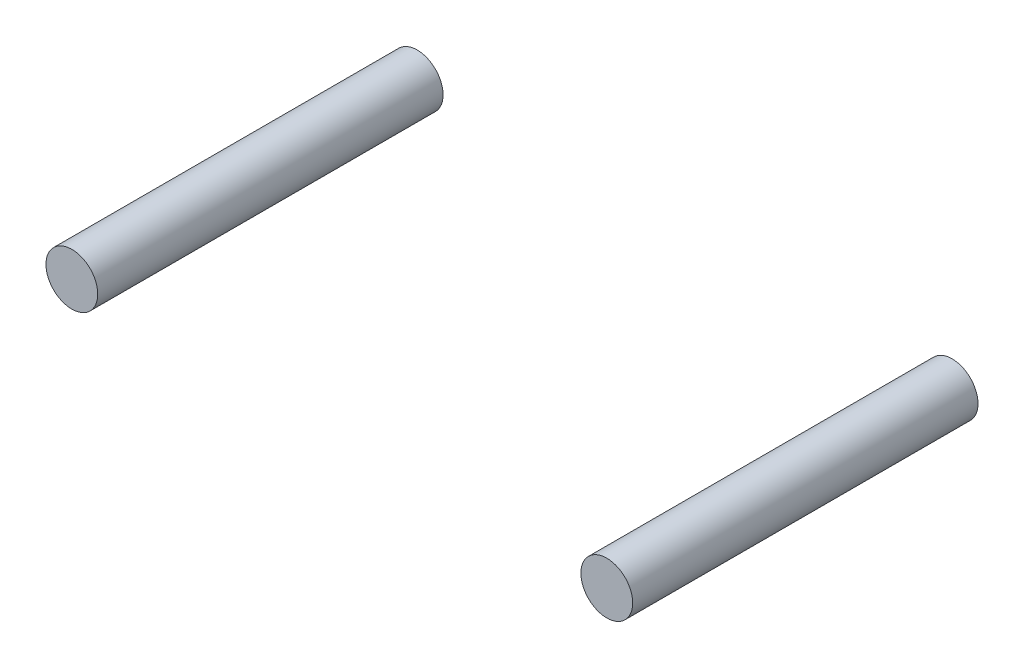
SolidWorks part; units mm, degrees
material "Brass"
ref_plane "Front Plane" through (0, 0, 0) normal (0, 0, 1) x (1, 0, 0)
ref_plane "Top Plane" through (0, 0, 0) normal (0, 1, 0) x (1, 0, 0)
ref_plane "Right Plane" through (0, 0, 0) normal (1, 0, 0) x (0, 0, -1)
sketch "Sketch1" plane through (0, 0, 0) normal (0, 0, 1) x (1, 0, 0)
  line L0 (0, -21.2809) -> (0, 20.8576) construction
  line L1 (-23.4901, 0) -> (24.9244, 0) construction
  line L2 (0, 0) -> (5.5969, 9.6942) construction
  line L3 (0, 0) -> (-5.6466, 9.7801) construction
  line L4 (2.05, 3.5507) -> (-1.6508, 5.6874) construction
  line L5 (-2.05, 3.5507) -> (1.6508, 5.6874) construction
  line L6 (0.8318, 0.175) -> (2.7945, 0.175)
  line L7 (0.8318, -0.175) -> (2.7945, -0.175)
  line L8 (-0.175, 0.8318) -> (-0.175, 2.7945)
  line L9 (0.175, 0.8318) -> (0.175, 2.7945)
  line L10 (0.175, -0.8318) -> (0.175, -2.7945)
  line L11 (-0.175, -0.8318) -> (-0.175, -2.7945)
  line L12 (-0.8318, -0.175) -> (-2.7945, -0.175)
  line L13 (-0.8318, 0.175) -> (-2.7945, 0.175)
  line L14 (0, 0) -> (6.6911, 7.6973) construction
  line L15 (0, 0) -> (-6.6911, 7.6973) construction
  line L16 (0, 4.7343) -> (6.5895, 2.1386) construction
  line L17 (2.6898, 3.0943) -> (2.2024, 3.8667)
  line L18 (0, 0) -> (2.5071, 3.384) construction
  line L19 (2.5071, 3.384) -> (2.4713, 3.3358)
  line L20 (2.6898, 3.0943) -> (1.7172, 2.6408)
  line L21 (3.6667, 2.0717) -> (3.6145, 2.0422)
  line L22 (3.7159, 1.7327) -> (3.5847, 2.6366)
  line L23 (3.7159, 1.7327) -> (2.6429, 1.714)
  line L24 (4.1923, 0.4012) -> (4.1326, 0.3955)
  line L25 (4.0994, 0.0716) -> (4.3472, 0.9506)
  line L26 (4.0994, 0.0716) -> (3.1115, 0.4909)
  line L27 (3.9931, -1.3387) -> (3.9362, -1.3196)
  line L28 (3.7741, -1.602) -> (4.3581, -0.8998)
  line L29 (3.7741, -1.602) -> (3.0422, -0.8171)
  line L30 (3.1034, -2.847) -> (3.0592, -2.8065)
  line L31 (2.7962, -2.9986) -> (3.6153, -2.5945)
  line L32 (2.7962, -2.9986) -> (2.4468, -1.9838)
  line L33 (1.6771, -3.8632) -> (1.6532, -3.8081)
  line L34 (1.3348, -3.8766) -> (2.2475, -3.8407)
  line L35 (1.3348, -3.8766) -> (1.4284, -2.8075)
  line L36 (-0.0392, -4.2113) -> (-0.0387, -4.1513)
  line L37 (-0.3573, -4.0844) -> (0.491, -4.4228)
  line L38 (-0.3573, -4.0844) -> (0.1629, -3.1458)
  line L39 (-1.7487, -3.8313) -> (-1.7238, -3.7767)
  line L40 (-1.9877, -3.5859) -> (-1.3504, -4.2401)
  line L41 (-1.9877, -3.5859) -> (-1.1306, -2.9401)
  line L42 (-3.1558, -2.7888) -> (-3.1109, -2.749)
  line L43 (-3.2744, -2.4674) -> (-2.9582, -3.3243)
  line L44 (-3.2744, -2.4674) -> (-2.2287, -2.226)
  line L45 (-4.0173, -1.2641) -> (-3.9601, -1.2461)
  line L46 (-3.9949, -0.9223) -> (-4.0546, -1.8337)
  line L47 (-3.9949, -0.9223) -> (-2.9415, -1.1271)
  line L48 (-4.1841, 0.4792) -> (-4.1245, 0.4724)
  line L49 (-4.0247, 0.7823) -> (-4.4499, -0.026)
  line L50 (-4.0247, 0.7823) -> (-3.1456, 0.1668)
  line L51 (-3.6275, 2.1396) -> (-3.5758, 2.1091)
  line L52 (-3.3585, 2.3517) -> (-4.0757, 1.7862)
  line L53 (-3.3585, 2.3517) -> (-2.8058, 1.4318)
  line L54 (-2.4436, 3.4301) -> (-2.4088, 3.3812)
  line L55 (-2.1117, 3.5144) -> (-2.9969, 3.2895)
  line L56 (-2.1117, 3.5144) -> (-1.9809, 2.4492)
  line L57 (-0.8372, 4.1274) -> (-0.8253, 4.0686)
  line L58 (-0.4997, 4.0694) -> (-1.3998, 4.2241)
  line L59 (-0.4997, 4.0694) -> (-0.8134, 3.0432)
  line L60 (0.9139, 4.1111) -> (0.9009, 4.0525)
  line L61 (1.1987, 3.9208) -> (0.4393, 4.4282)
  line L62 (1.1987, 3.9208) -> (0.4947, 3.1109)
  line L63 (0, 4.7343) -> (-2.5531, 3.1697) construction
  line L64 (-2.05, 3.5507) -> (-2.4328, 4.7289) construction
  line L65 (-2.0183, 3.4974) -> (-2.5292, 5.0699)
  line L66 (2.5071, 4.3424) -> (3.1715, 5.3462) construction
  line L67 (2.2024, 3.8667) -> (3.1115, 5.2402)
  line L68 (2.5071, 3.384) -> (3.5557, 4.9683)
  line L69 (3.5557, 4.9683) -> (3.1115, 5.2402)
  line L70 (-2.5292, 5.0699) -> (-2.0347, 5.2306)
  line L71 (-2.0347, 5.2306) -> (-1.4785, 3.5187)
  line L72 (-2.1117, 3.5144) -> (-1.2626, 3.7301) construction
  line L73 (-2.0183, 3.4974) -> (-1.4785, 3.5187)
  line L74 (0, 4.7343) -> (-0.7323, 13.1045) construction
  line L75 (3.1336, 5.4612) -> (3.7485, 5.0848)
  line L76 (3.7797, 4.9444) -> (3.2146, 4.0906)
  line L77 (2.998, 5.4311) -> (2.9748, 5.396)
  line L78 (0.067, 6.2631) -> (0.1001, 5.8849)
  line L79 (3.2146, 4.0906) -> (2.93, 3.9142)
  line L80 (2.93, 3.9142) -> (2.88, 3.9474)
  line L81 (-2.6861, 5.2292) -> (-2.0014, 5.4517)
  line L82 (-1.8754, 5.3875) -> (-1.7926, 5.1326)
  line L83 (-2.7504, 5.1032) -> (-2.4797, 4.2702)
  line L84 (-2.4797, 4.2702) -> (-2.2599, 4.0467)
  line L85 (-2.2599, 4.0467) -> (-2.2028, 4.0652)
  line L86 (-0.3315, 6.2283) -> (-0.2984, 5.85)
  line L87 (0.067, 6.2631) -> (-0.31, 10.5723)
  line L88 (-0.3315, 6.2283) -> (-0.7085, 10.5374)
  line L89 (0, 4.7343) -> (-1.8171, 12.9313) construction
  line L90 (0, 13.1343) -> (-1.0909, 9.5661) construction
  line L91 (-0.2672, 11.2304) -> (-0.2957, 11.5563)
  line L92 (-0.8649, 11.1781) -> (-0.8934, 11.504)
  line L93 (-0.8649, 11.1781) -> (-0.2672, 11.2304)
  line L94 (-0.5939, 10.5474) -> (-0.4246, 10.5622)
  line L95 (-0.4246, 10.5622) -> (-0.5425, 11.9099)
  line L96 (-0.5425, 11.9099) -> (-0.64, 12.0491)
  line L97 (-0.5939, 10.5474) -> (-0.7118, 11.895)
  line L98 (-0.7118, 11.895) -> (-0.64, 12.0491)
  line L99 (-0.3654, 10.9187) -> (-0.3218, 10.4206)
  line L100 (-0.3218, 10.4206) -> (-0.6705, 10.3901)
  line L101 (-0.6705, 10.3901) -> (-0.7141, 10.8882)
  line L102 (-0.7141, 10.8882) -> (-0.3654, 10.9187)
  circle A0 centre (0, 0) radius 4.1
  circle A1 centre (0, 4.7343) radius 0.25
  circle A2 centre (0, 0) radius 0.35
  arc A3 (-0.175, 0.8318) -> (-0.8318, 0.175) centre (0, 0) ccw
  arc A4 (-0.175, 2.7945) -> (-2.7945, 0.175) centre (0, 0) ccw
  arc A5 (0.6577, 3.0806) -> (0.4947, 3.1109) centre (0, 0) ccw
  arc A6 (-0.8318, -0.175) -> (-0.175, -0.8318) centre (0, 0) ccw
  arc A7 (0.8318, 0.175) -> (0.175, 0.8318) centre (0, 0) ccw
  arc A8 (0.175, -0.8318) -> (0.8318, -0.175) centre (0, 0) ccw
  arc A9 (-2.7945, -0.175) -> (-0.175, -2.7945) centre (0, 0) ccw
  arc A10 (2.7945, 0.175) -> (0.175, 2.7945) centre (0, 0) ccw
  arc A11 (0.175, -2.7945) -> (2.7945, -0.175) centre (0, 0) ccw
  arc A12 (2.05, 3.5507) -> (1.8799, 6.1728) centre (0, 4.7343) ccw
  circle A13 centre (0, 0) radius 4.2115
  arc A14 (2.4713, 3.3358) -> (2.4182, 3.0865) centre (2.388, 3.2233) cw
  arc A15 (0.6577, 3.0806) -> (2.4182, 3.0865) centre (1.5242, 7.1391) ccw
  arc A16 (1.8538, 2.5467) -> (3.4645, 1.8361) centre (4.2961, 5.902) ccw
  arc A17 (2.7628, 3.1783) -> (2.7631, 3.1784) centre (1.5242, 7.1391) ccw
  arc A18 (3.6145, 2.0422) -> (3.4645, 1.8361) centre (3.4926, 1.9733) cw
  arc A19 (2.7294, 1.5725) -> (3.9118, 0.2683) centre (6.3253, 3.6443) ccw
  arc A20 (4.1326, 0.3955) -> (3.9118, 0.2683) centre (3.9932, 0.3821) cw
  arc A21 (3.133, 0.3264) -> (3.6827, -1.346) centre (7.2607, 0.7565) ccw
  arc A22 (3.9362, -1.3196) -> (3.6827, -1.346) centre (3.8034, -1.2751) cw
  arc A23 (2.995, -0.9761) -> (2.8169, -2.7275) centre (6.9407, -2.2621) ccw
  arc A24 (3.0592, -2.8065) -> (2.8169, -2.7275) centre (2.956, -2.7118) cw
  arc A25 (2.339, -2.1099) -> (1.4639, -3.6375) centre (5.4206, -4.8895) ccw
  arc A26 (1.6532, -3.8081) -> (1.4639, -3.6375) centre (1.5974, -3.6797) cw
  arc A27 (1.2786, -2.8788) -> (-0.1421, -3.9184) centre (2.9632, -6.6715) ccw
  arc A28 (-0.0387, -4.1513) -> (-0.1421, -3.9184) centre (-0.0374, -4.0113) cw
  arc A29 (-0.0028, -3.15) -> (-1.7236, -3.5219) centre (-0.0066, -7.3) ccw
  arc A30 (-1.7238, -3.7767) -> (-1.7236, -3.5219) centre (-1.6657, -3.6493) cw
  arc A31 (-1.2838, -2.8765) -> (-3.007, -2.5163) centre (-2.9752, -6.6662) ccw
  arc A32 (-3.1109, -2.749) -> (-3.007, -2.5163) centre (-3.006, -2.6563) cw
  arc A33 (-2.3428, -2.1057) -> (-3.7706, -1.0757) centre (-5.4293, -4.8798) ccw
  arc A34 (-3.9601, -1.2461) -> (-3.7706, -1.0757) centre (-3.8265, -1.204) cw
  arc A35 (-2.9967, -0.9707) -> (-3.8821, 0.5509) centre (-6.9447, -2.2496) ccw
  arc A36 (-4.1245, 0.4724) -> (-3.8821, 0.5509) centre (-3.9854, 0.4564) cw
  arc A37 (-3.1324, 0.3321) -> (-3.3224, 2.0823) centre (-7.2593, 0.7696) ccw
  arc A38 (-3.5758, 2.1091) -> (-3.3224, 2.0823) centre (-3.4552, 2.038) cw
  arc A39 (-2.7266, 1.5775) -> (-2.1882, 3.2536) centre (-6.3187, 3.6557) ccw
  arc A40 (-2.4088, 3.3812) -> (-2.1882, 3.2536) centre (-2.3276, 3.2672) cw
  arc A41 (-1.8492, 2.5501) -> (-0.6757, 3.8623) centre (-4.2855, 5.9097) ccw
  arc A42 (-0.8253, 4.0686) -> (-0.6757, 3.8623) centre (-0.7975, 3.9314) cw
  arc A43 (-0.6522, 3.0818) -> (0.9537, 3.8033) centre (-1.5113, 7.1418) ccw
  arc A44 (0.9009, 4.0525) -> (0.9537, 3.8033) centre (0.8705, 3.9159) cw
  arc A45 (2.0666, 2.3773) -> (1.575, 2.728) centre (0, 0) ccw
  arc A46 (2.7294, 1.5725) -> (2.6429, 1.714) centre (0, 0) ccw
  arc A47 (3.133, 0.3264) -> (3.1115, 0.4909) centre (0, 0) ccw
  arc A48 (2.995, -0.9761) -> (3.0422, -0.8171) centre (0, 0) ccw
  arc A49 (2.339, -2.1099) -> (2.4468, -1.9838) centre (0, 0) ccw
  arc A50 (-0.6522, 3.0818) -> (-0.8134, 3.0432) centre (0, 0) ccw
  arc A51 (-1.575, 2.728) -> (-2.0666, 2.3773) centre (0, 0) ccw
  arc A52 (-2.7266, 1.5775) -> (-2.8058, 1.4318) centre (0, 0) ccw
  arc A53 (-3.1324, 0.3321) -> (-3.1456, 0.1668) centre (0, 0) ccw
  arc A54 (-2.9967, -0.9707) -> (-2.9415, -1.1271) centre (0, 0) ccw
  arc A55 (-2.3428, -2.1057) -> (-2.2287, -2.226) centre (0, 0) ccw
  arc A56 (-1.2838, -2.8765) -> (-1.1306, -2.9401) centre (0, 0) ccw
  arc A57 (-0.0028, -3.15) -> (0.1629, -3.1458) centre (0, 0) ccw
  arc A58 (1.2786, -2.8788) -> (1.4284, -2.8075) centre (0, 0) ccw
  arc A59 (-2.05, 3.5507) -> (-0.5036, 2.4213) centre (0, 4.7343) ccw
  arc A60 (1.0177, 5.1638) -> (2.0583, 5.0774) centre (1.3569, 2.9395) cw
  arc A61 (0.2412, 4.4152) -> (2.5336, 4.367) centre (1.3569, 2.9395) cw
  arc A62 (-0.2238, 4.4028) -> (-1.7102, 4.232) centre (-0.8673, 3.4497) ccw
  arc A63 (3.7485, 5.0848) -> (3.7797, 4.9444) centre (3.6963, 4.9996) cw
  arc A64 (2.998, 5.4311) -> (3.1336, 5.4612) centre (3.0814, 5.3759) cw
  arc A65 (-0.2238, 4.4028) -> (0.2412, 4.4152) centre (0, 4.7343) ccw
  arc A66 (2.9748, 5.396) -> (2.0583, 5.0774) centre (2.3077, 5.8375) cw
  arc A67 (1.0177, 5.1638) -> (0.1001, 5.8849) centre (0.8971, 5.9546) cw
  arc A68 (-1.8754, 5.3875) -> (-2.0014, 5.4517) centre (-1.9705, 5.3566) ccw
  arc A69 (-2.7504, 5.1032) -> (-2.6861, 5.2292) centre (-2.6552, 5.1341) cw
  arc A70 (-0.2984, 5.85) -> (-0.754, 5.1723) centre (-0.9459, 5.7934) cw
  arc A71 (-1.7926, 5.1326) -> (-1.5095, 5.0037) centre (-1.5211, 5.3535) ccw
  arc A72 (-0.31, 10.5723) -> (-0.0079, 11.1276) centre (0.2577, 10.6233) cw
  arc A73 (-0.0652, 5.4791) -> (0, 5.5041) centre (-2.8729, 12.8867) ccw
  arc A74 (-1.5095, 5.0037) -> (-0.754, 5.1723) centre (-2.8729, 12.8867) ccw
  arc A75 (-0.0079, 11.1276) -> (0.0594, 11.5321) centre (0.4209, 11.2641) cw
  arc A76 (0.0594, 11.5321) -> (0.2329, 11.9395) centre (-0.7039, 12.0977) ccw
  arc A77 (-0.3152, 11.3278) -> (-0.8812, 11.5261) centre (-0.5952, 11.4355) ccw
  circle A78 centre (0, 13.1343) radius 1.2
  circle A79 centre (0, 13.1343) radius 2
  arc A80 (-0.7085, 10.5374) -> (-1.1024, 11.0318) centre (-1.2764, 10.489) ccw
  arc A81 (-1.1024, 11.0318) -> (-1.2389, 11.4185) centre (-1.5484, 11.0918) ccw
  arc A82 (-1.2389, 11.4185) -> (-1.4805, 11.7896) centre (-0.5855, 12.1081) cw
  arc A83 (-1.4805, 11.7896) -> (-0.8934, 11.504) centre (-0.6802, 12.6886) ccw
  arc A84 (0.2329, 11.9395) -> (-0.2957, 11.5563) centre (-0.7114, 12.6858) cw
  circle A85 centre (0, 13.1343) radius 1.8
  arc A86 (-0.8715, 11.5024) -> (-0.3375, 11.3153) centre (0, 13.1343) ccw
  arc A87 (-0.3375, 11.3153) -> (-0.3152, 11.3278) centre (-0.3338, 11.335) ccw
  circle A88 centre (0, 13.1343) radius 1.85 construction
  arc A89 (-0.8789, 11.3381) -> (-0.8787, 11.3377) centre (-0.5952, 11.4355) ccw
  arc A90 (-0.8715, 11.5024) -> (-0.8812, 11.5261) centre (-0.8621, 11.5201) cw
  circle A91 centre (0, 13.1343) radius 0.4
  circle A92 centre (0, 4.7343) radius 5.75
  circle A93 centre (-0.7745, 10.4319) radius 0.075
  circle A94 centre (0.7745, 10.4319) radius 0.075
  point P36 (0, 0)
  point P40 (2.5071, 3.384)
  point P180 (0, 0)
  point P182 (-2.0183, 3.4974)
  point P245 (0, 13.1343)
  point P252 (-0.5661, 11.2043)
  point P268 (-0.5661, 11.2043)
  point P273 (-0.5092, 10.5548)
  point P276 (1.85, 13.1343)
  dimension "D1" = 8.2
  dimension "D4" = 0.5
  dimension "D5" = 0.7
  dimension "D6" = 1.7
  dimension "D7" = 5.6
  dimension "D8" = 6.3
  dimension "D17" = 0.14
  dimension "D18" = 8.3
  dimension "D28" = 0.4
  dimension "D29" = 1.85
  dimension "D31" = 1.15
  dimension "D34" = 2.25
  dimension "D37" = 0.1
  dimension "D39" = 0.1
  dimension "D40" = 0.8
  dimension "D41" = 0.8
  dimension "D46" = 0.1
  dimension "D48" = 0.1
  dimension "D52" = 0.35
  dimension "D53" = 0.65
  dimension "D54" = 0.2
  dimension "D55" = 0.95
  dimension "D56" = 0.45
  dimension "D57" = 0.57
  dimension "D58" = 0.2375
  dimension "D61" = 0.6
  dimension "D62" = 2.4
  dimension "D64" = 4
  dimension "D65" = 3.6
  dimension "D70" = 0.05
  dimension "D71" = 0.02
  dimension "D76" = 0.8
  dimension "D77" = 11.5
  dimension "D78" = 0.15
  dimension "D2" = 60
  dimension "D3" = 30
  dimension "D9" = 0.35
  dimension "D11" = 11
  dimension "D12" = 8.5
  dimension "D13" = 0.9133
  dimension "D14" = 0.3425
  dimension "D15" = 0.06
  dimension "D16" = 24
  dimension "D20" = 1.5
  dimension "D21" = 12
  dimension "D22" = 1.8
  dimension "D23" = 3.5
  dimension "D24" = 1.6471
  dimension "D25" = 1.9
  dimension "D26" = 0.52
  dimension "D27" = 12
  dimension "D30" = 0.6
  dimension "D32" = 0.75
  dimension "D33" = 5
  dimension "D35" = 0.2
  dimension "D36" = 0.2
  dimension "D38" = 0.2
  dimension "D42" = 0.06
  dimension "D43" = 1
  dimension "D44" = 0.2
  dimension "D45" = 0.2
  dimension "D47" = 0.2
  dimension "D49" = 0.9
  dimension "D50" = 0.6
  dimension "D51" = 0.06
  dimension "D59" = 1.93
  dimension "D60" = 8.4
  dimension "D63" = 17
  dimension "D66" = 0.17
  dimension "D67" = 1.5
  dimension "D68" = 30
  dimension "D69" = 0.6
  dimension "D72" = 0.35
  dimension "D73" = 0.175
  dimension "D74" = 0.5
  dimension "D75" = 0.15
  dimension "D10" = 4
  dimension "D19" = 15
extrude "Boss-Extrude1" add sketch "Sketch1" along normal mid plane 1 contours A93 A92 | A92 A93 | A94 A92 | A94 A92
equation "\"D14@Sketch1\"=\"D13@Sketch1\"*3/8"
